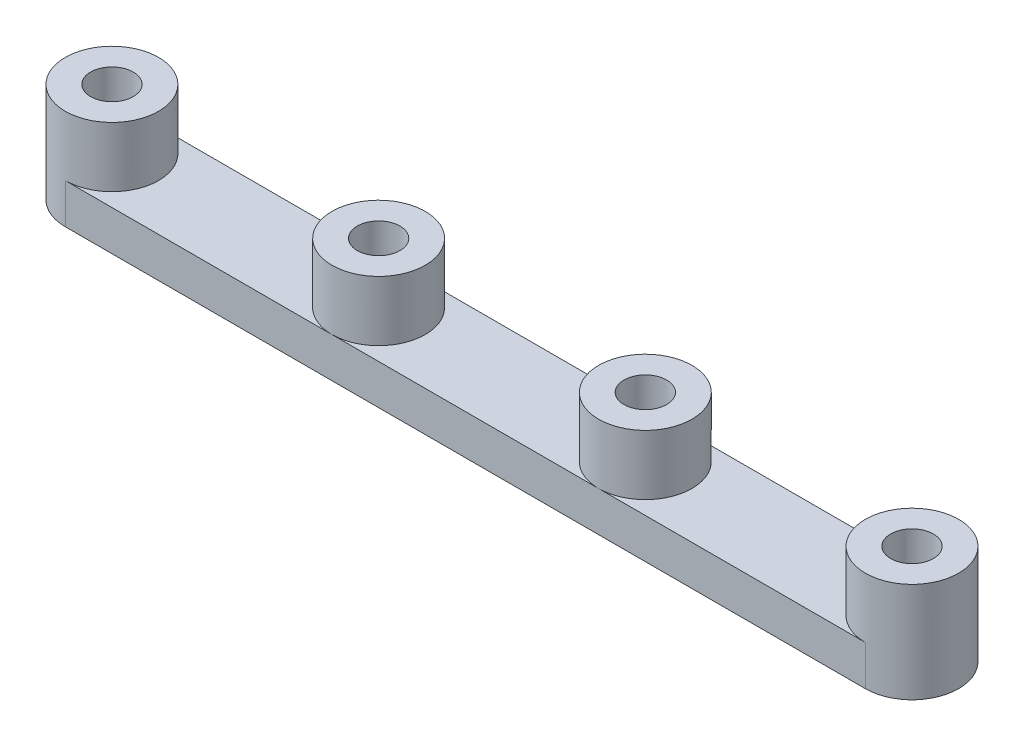
SolidWorks part; units mm, degrees
ref_plane "Front Plane" through (0, 0, 0) normal (0, 0, 1) x (1, 0, 0)
ref_plane "Top Plane" through (0, 0, 0) normal (0, 1, 0) x (1, 0, 0)
ref_plane "Right Plane" through (0, 0, 0) normal (1, 0, 0) x (0, 0, -1)
sketch "Sketch1" plane through (0, 0, 0) normal (0, 1, 0) x (1, 0, 0)
  line L0 (30, 0) -> (-30, 0) construction
  line L1 (30, -3.5) -> (-30, -3.5)
  line L2 (30, 3.5) -> (-30, 3.5)
  arc A0 (30, -3.5) -> (30, 3.5) centre (30, 0) ccw
  arc A1 (-30, 3.5) -> (-30, -3.5) centre (-30, 0) ccw
  circle A2 centre (-30, 0) radius 1.6
  circle A3 centre (-10, 0) radius 1.6
  circle A4 centre (10, 0) radius 1.6
  circle A5 centre (30, 0) radius 1.6
  point P2 (0, 0)
  dimension "D2" = 3.5
  dimension "D5" = 3.2
  dimension "D1" = 60
  dimension "D3" = 20
  dimension "D4" = 20
extrude "Boss-Extrude1" add sketch "Sketch1" along normal blind 3
sketch "Sketch2" plane through (0, 3, 0) normal (0, 1, 0) x (1, 0, 0)
  circle A0 centre (-30, 0) radius 3.5
  circle A1 centre (-10, 0) radius 3.5
  circle A2 centre (10, 0) radius 3.5
  circle A3 centre (30, 0) radius 3.5
  circle A4 centre (-30, 0) radius 1.6
  circle A5 centre (-10, 0) radius 1.6
  circle A6 centre (10, 0) radius 1.6
  circle A7 centre (30, 0) radius 1.6
  dimension "D1" = 3.2
extrude "Boss-Extrude2" add sketch "Sketch2" along normal blind 4.5
